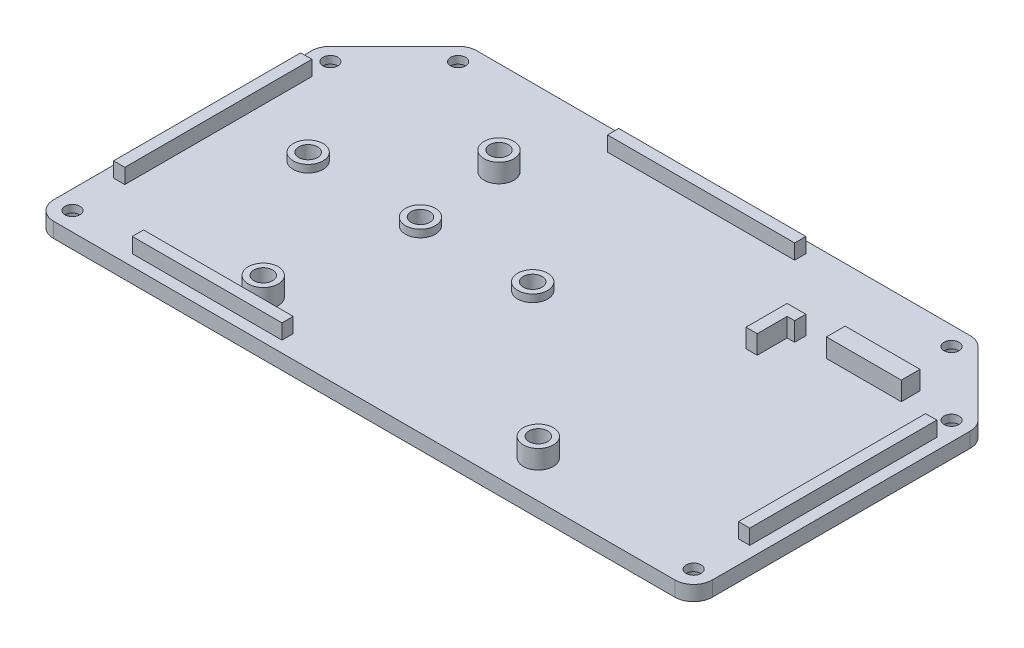
SolidWorks part; units mm, degrees
ref_plane "Front Plane" through (0, 0, 0) normal (0, 0, 1) x (1, 0, 0)
ref_plane "Top Plane" through (0, 0, 0) normal (0, 1, 0) x (1, 0, 0)
ref_plane "Right Plane" through (0, 0, 0) normal (1, 0, 0) x (0, 0, -1)
sketch "Sketch1" plane through (0, 0, 0) normal (0, 1, 0) x (1, 0, 0)
  line L0 (-88, 28) -> (-68, 48)
  line L1 (88, -48) -> (-88, -48)
  line L2 (88, -48) -> (88, 48)
  line L3 (88, 48) -> (-88, 48)
  line L4 (-88, -48) -> (-88, 48)
  line L5 (88, -48) -> (-88, 48) construction
  line L6 (88, 48) -> (-88, -48) construction
  line L7 (0, 48) -> (0, -48) construction
  line L8 (88, 28) -> (68, 48)
  point P0 (0, 0)
  dimension "D1" = 176
  dimension "D2" = 96
  dimension "D3" = 20
  dimension "D4" = 20
extrude "Boss-Extrude1" add sketch "Sketch1" along normal blind 4 contours L2 L8 L3 L0 L4 L1
sketch "Sketch10" plane through (0, 4, 0) normal (0, 1, 0) x (1, 0, 0)
  line L0 (88, 28) -> (68, 48) construction
  line L1 (88, -48) -> (88, 28) construction
  line L2 (88, -48) -> (-88, -48) construction
  line L3 (-88, -48) -> (-88, 28) construction
  line L4 (68, 48) -> (-68, 48) construction
  line L5 (-88, 28) -> (-68, 48) construction
  line L6 (88, 28) -> (68, 48)
  line L7 (88, -48) -> (88, 28)
  line L8 (88, -48) -> (-88, -48)
  line L9 (-88, -48) -> (-88, 28)
  line L10 (68, 48) -> (-68, 48)
  line L11 (-88, 28) -> (-68, 48)
  line L12 (-85, 26.7574) -> (-66.7574, 45)
  line L13 (66.7574, 45) -> (-66.7574, 45)
  line L14 (85, 26.7574) -> (66.7574, 45)
  line L15 (85, -45) -> (85, 26.7574)
  line L16 (85, -45) -> (-85, -45)
  line L17 (-85, -45) -> (-85, 26.7574)
  line L19 (43, 22) -> (81, 22) construction
  line L20 (43, 22) -> (43, -41) construction
  line L21 (43, -41) -> (81, -41) construction
  line L22 (81, 22) -> (81, -41) construction
  line L23 (43, 22) -> (81, -41) construction
  line L24 (43, -41) -> (81, 22) construction
  line L25 (-39.5, 27) -> (38.5, 27) construction
  line L26 (-39.5, 27) -> (-39.5, -41) construction
  line L27 (-39.5, -41) -> (38.5, -41) construction
  line L28 (38.5, 27) -> (38.5, -41) construction
  line L29 (72, 23.5) -> (52, 23.5)
  line L30 (72, 23.5) -> (72, 28.5)
  line L31 (72, 28.5) -> (52, 28.5)
  line L32 (52, 23.5) -> (52, 28.5)
  line L33 (72, 23.5) -> (52, 28.5) construction
  line L34 (72, 28.5) -> (52, 23.5) construction
  line L35 (42, 23) -> (42, 15)
  line L36 (42, 15) -> (39, 15)
  line L37 (39, 15) -> (39, 26)
  line L38 (39, 26) -> (44, 26)
  line L39 (44, 26) -> (44, 23)
  line L40 (42, 23) -> (44, 23)
  circle A0 centre (-35, 23) radius 2.5
  circle A1 centre (-37.5, -37.5) radius 2.5
  circle A2 centre (36.5, -38) radius 2.5
  circle A3 centre (-35, 23) radius 4
  circle A4 centre (-37.5, -37.5) radius 4
  circle A5 centre (36.5, -38) radius 4
  point P12 (62, -9.5)
  point P17 (-0.5, -2.6565)
  point P28 (62, 26)
  dimension "D9" = 5
  dimension "D26" = 8
  dimension "D2" = 38
  dimension "D3" = 63
  dimension "D4" = 78
  dimension "D5" = 2
  dimension "D6" = 3.5
  dimension "D7" = 4.5
  dimension "D8" = 4
  dimension "D10" = 2
  dimension "D11" = 3
  dimension "D12" = 4
  dimension "D13" = 50
  dimension "D14" = 68
  dimension "D15" = 4
  dimension "D16" = 4
  dimension "D17" = 5
  dimension "D18" = 20
  dimension "D19" = 3
  dimension "D20" = 1
  dimension "D21" = 1
  dimension "D22" = 8
  dimension "D23" = 3
  dimension "D24" = 5
  dimension "D25" = 3
  dimension "D1" = 3
extrude "Boss-Extrude5" add sketch "Sketch10" along normal blind 5 contours A5 A2 | A4 A1 | A3 A0 | L32 L29 L30 L31 | L35 L40 L39 L38 L37 L36
sketch "Sketch11" plane through (0, 4, 0) normal (0, 1, 0) x (1, 0, 0)
  line L0 (68, 48) -> (-68, 48) construction
  line L1 (-83.5, 20) -> (-85, 20)
  line L2 (-85, 20) -> (-82, 20)
  line L4 (-88, 28) -> (-68, 48) construction
  line L5 (-25, -45) -> (-65, -45)
  line L10 (-88, 28) -> (-68, 48) construction
  line L13 (25, 45) -> (-25, 45)
  line L17 (-85, -30) -> (-85, 20)
  line L18 (25, 42) -> (-25, 42)
  line L20 (-82, -30) -> (-82, 20)
  line L24 (88, -48) -> (-88, -48) construction
  line L25 (-65, -45) -> (-65, -42)
  line L26 (-25, 43.5) -> (-25, 45)
  line L27 (-25, 45) -> (-25, 42)
  line L28 (25, 43.5) -> (25, 45)
  line L29 (25, 45) -> (25, 42)
  line L30 (25, -45) -> (25, -42)
  line L31 (65.5147, 42) -> (-65.5147, 42) construction
  line L32 (66.7574, 45) -> (-66.7574, 45) construction
  line L33 (85, 20) -> (82, 20)
  line L34 (-85, -30) -> (-82, -30)
  line L35 (0, 0) -> (0, 23.0218) construction
  line L36 (0, 23.0218) -> (0, 0) construction
  line L37 (0, 0) -> (-16.9506, 0) construction
  line L38 (85, -30) -> (82, -30)
  line L40 (25, -45) -> (25, -42)
  line L41 (25, -43.5) -> (25, -45)
  line L42 (-25, -45) -> (-25, -42)
  line L43 (-25, -43.5) -> (-25, -45)
  line L44 (82, -42) -> (-82, -42) construction
  line L45 (85, -45) -> (-85, -45) construction
  line L46 (88, -48) -> (-88, -48) construction
  line L47 (-82, -42) -> (-82, 25.5147) construction
  line L48 (-85, -45) -> (-85, 26.7574) construction
  line L49 (-88, -48) -> (-88, 28) construction
  line L50 (82, -42) -> (82, 25.5147) construction
  line L51 (85, -45) -> (85, 26.7574) construction
  line L52 (88, -48) -> (88, 28) construction
  line L53 (-82, 25.5147) -> (-65.5147, 42) construction
  line L54 (-85, 26.7574) -> (-66.7574, 45) construction
  line L55 (68, 48) -> (-68, 48) construction
  line L56 (82, 25.5147) -> (65.5147, 42) construction
  line L57 (85, 26.7574) -> (66.7574, 45) construction
  line L58 (88, 28) -> (68, 48) construction
  line L59 (85, -30) -> (85, 20)
  line L60 (82, -30) -> (82, 20)
  line L61 (45, -42) -> (45, -45)
  line L62 (-25, -42) -> (-65, -42)
  line L64 (25, -45) -> (45, -45)
  line L65 (25, -42) -> (45, -42)
  point P27 (0, 42)
  dimension "D3" = 50
  dimension "D1" = 3
  dimension "D2" = 6
  dimension "D4" = 18
  dimension "D5" = 28
  dimension "D6" = 50
  dimension "D7" = 40
  dimension "D8" = 20
  dimension "D9" = 70
extrude "Boss-Extrude6" add sketch "Sketch11" along normal blind 4 contours L29 L28 L13 L26 L27 L18 | L17 L34 L20 L2 L1 | L60 L38 L59 L33 | L5 L25 L62 L42
sketch "Sketch12" plane through (0, 4, 0) normal (0, 1, 0) x (1, 0, 0)
  line L0 (-88, 0) -> (88, 0) construction
  line L1 (-88, -48) -> (-88, 28) construction
  line L2 (88, -48) -> (88, 28) construction
  circle A0 centre (-63, 0) radius 2.5
  circle A1 centre (-33, 0) radius 2.5
  circle A2 centre (-3, 0) radius 2.5
  point P13 (0, 0)
  point P14 (0, 0)
  dimension "D4" = 5
  dimension "D1" = 25
  dimension "D2" = 30
  dimension "D3" = 30
extrude "Cut-Extrude5" cut sketch "Sketch12" against normal blind 4
sketch "Sketch13" plane through (0, 4, 0) normal (0, 1, 0) x (1, 0, 0)
  circle A0 centre (-63, 0) radius 2.5
  circle A1 centre (-33, 0) radius 2.5
  circle A2 centre (-3, 0) radius 2.5
  circle A3 centre (-63, 0) radius 4
  circle A4 centre (-33, 0) radius 4
  circle A5 centre (-3, 0) radius 4
  dimension "D1" = 5
  dimension "D2" = 8
extrude "Boss-Extrude7" add sketch "Sketch13" along normal blind 2
sketch "Sketch14" plane through (0, 4, 0) normal (0, 1, 0) x (1, 0, 0)
  line L0 (-88, 20.9289) -> (-60.9289, 48) construction
  line L1 (-88, -48) -> (-88, 28) construction
  line L2 (68, 48) -> (-68, 48) construction
  line L3 (-88, 28) -> (-68, 48) construction
  line L4 (88, -48) -> (-88, -48) construction
  line L5 (0, 48) -> (0, -48) construction
  circle A0 centre (-65.9289, 43) radius 2
  circle A1 centre (-83, 25.9289) radius 2
  circle A2 centre (-83, -43) radius 2
  circle A3 centre (65.9289, 43) radius 2
  circle A4 centre (83, 25.9289) radius 2
  circle A5 centre (83, -43) radius 2
  dimension "D3" = 4
  dimension "D5" = 5
  dimension "D1" = 5
  dimension "D2" = 5
  dimension "D4" = 5
  dimension "D6" = 5
extrude "Cut-Extrude6" cut sketch "Sketch14" against normal blind 15
sketch "Sketch15" plane through (0, 0, 0) normal (0, -1, 0) x (1, 0, 0)
  line L0 (0, 0) -> (0, -48) construction
  line L1 (68, -48) -> (-68, -48) construction
  circle A0 centre (-83, 43) radius 3.5
  circle A1 centre (-83, -25.9289) radius 3.5
  circle A2 centre (-65.9289, -43) radius 3.5
  circle A3 centre (65.9289, -43) radius 3.5
  circle A4 centre (83, -25.9289) radius 3.5
  circle A5 centre (83, 43) radius 3.5
  dimension "D1" = 7
extrude "Cut-Extrude8" cut sketch "Sketch15" against normal blind 2
fillet "Fillet1" radius 5 6 edges at (88, 2, 48) (88, 2, -28) (68, 2, -48) (-68, 2, -48) (-88, 2, -28) (-88, 2, 48)
